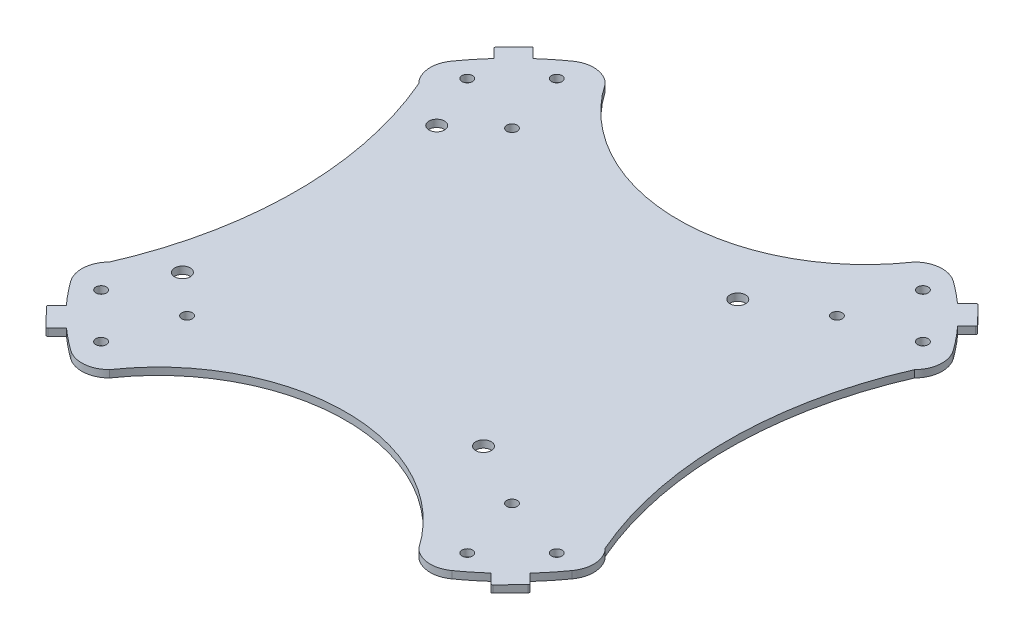
SolidWorks part; units mm, degrees
ref_plane "Front Plane" through (0, 0, 0) normal (0, 0, 1) x (1, 0, 0)
ref_plane "Top Plane" through (0, 0, 0) normal (0, 1, 0) x (1, 0, 0)
ref_plane "Right Plane" through (0, 0, 0) normal (1, 0, 0) x (0, 0, -1)
sketch "Sketch1" plane through (0, 0, 0) normal (0, 1, 0) x (1, 0, 0)
  line L0 (-1000, 0) -> (49000, 0) construction
  line L1 (0, -1000) -> (0, 49000) construction
  line L2 (707.1069, -707.1069) -> (-34648.2322, 34648.2322) construction
  line L3 (-707.1068, -707.1068) -> (34648.2325, 34648.2321) construction
  line L4 (716.0871, -698.1266) -> (0, 17.9605) construction
  line L5 (-698.1265, -716.087) -> (34657.2127, 34639.2518) construction
  line L6 (698.1266, -716.0871) -> (-34657.2125, 34639.2519) construction
  line L7 (-716.087, -698.1265) -> (0, 17.9605) construction
  line L8 (-733.6258, -670.2104) -> (-31.7077, 31.7077) construction
  line L9 (733.9751, -670.5597) -> (22.7274, 40.6879) construction
  line L10 (39.5829, 36.115) -> (36.1358, 39.5583) construction
  line L11 (716.0871, -698.1266) -> (-34639.2519, 34657.2125) construction
  line L12 (35.7817, 39.5534) -> (33.9856, 37.7573) construction
  line L13 (-716.087, -698.1265) -> (34639.2522, 34657.2124) construction
  line L14 (39.5739, 35.7609) -> (37.7573, 33.9856) construction
  line L15 (39.5382, -36.1548) -> (36.0819, -39.6111) construction
  line L16 (39.5078, -35.8322) -> (37.7118, -34.0362) construction
  line L17 (-35.9968, -39.6764) -> (-39.3444, -36.2512) construction
  line L18 (-37.6038, -34.1555) -> (-39.3423, -35.894) construction
  line L19 (35.7129, -39.6171) -> (33.9376, -37.8006) construction
  line L20 (-35.6141, -39.7036) -> (-33.8181, -37.9075) construction
  line L21 (-39.7221, 35.8999) -> (-36.251, 39.2922) construction
  line L22 (-34.2033, 37.5603) -> (-35.8918, 39.2881) construction
  line L24 (-37.9528, 33.7672) -> (-39.7242, 35.5386) construction
  line L25 (-44.6575, -41.2092) -> (-46.396, -42.9477)
  line L26 (-43.0506, -46.7302) -> (-46.3981, -43.3049)
  line L27 (-42.6678, -46.7573) -> (-40.8718, -44.9612)
  line L28 (42.6678, -46.7573) -> (40.8718, -44.9612)
  line L29 (43.0506, -46.7302) -> (46.3981, -43.3049)
  line L30 (-39.4203, -35.9308) -> (-37.6038, -34.1555) [skipped]
  line L31 (-39.7488, 35.5633) -> (-37.9528, 33.7672) [skipped]
  line L32 (-35.9786, 39.3768) -> (-34.2033, 37.5603) [skipped]
  line L33 (44.6575, -41.2092) -> (46.396, -42.9477)
  line L35 (-44.6575, 41.2092) -> (-46.396, 42.9477)
  line L36 (-43.0506, 46.7302) -> (-46.3981, 43.3049)
  line L37 (-42.6678, 46.7573) -> (-40.8718, 44.9612)
  line L38 (44.6575, 41.2092) -> (46.396, 42.9477)
  line L39 (43.0506, 46.7302) -> (46.3981, 43.3049)
  line L40 (42.6678, 46.7573) -> (40.8718, 44.9612)
  arc A0 (-29.6486, 41.2505) -> (-34.2033, 37.5603) centre (0, 0) ccw construction
  arc A1 (-22.7274, 40.6879) -> (-29.6486, 41.2505) centre (-26.519, 36.8963) ccw construction
  arc A2 (-40.6879, 22.7274) -> (-41.2505, 29.6486) centre (-36.8963, 26.519) cw construction
  arc A3 (22.7274, 40.6879) -> (29.6486, 41.2505) centre (26.519, 36.8963) cw construction
  arc A4 (40.6879, 22.7274) -> (41.2505, 29.6486) centre (36.8963, 26.519) ccw construction
  arc A5 (40.6879, -22.7274) -> (41.2505, -29.6486) centre (36.8963, -26.519) cw construction
  arc A6 (22.7274, -40.6879) -> (29.6486, -41.2505) centre (26.519, -36.8963) ccw construction
  arc A7 (-22.7274, -40.6879) -> (-29.6486, -41.2505) centre (-26.519, -36.8963) cw construction
  arc A8 (-40.6879, -22.7274) -> (-41.2505, -29.6486) centre (-36.8963, -26.519) ccw construction
  arc A9 (-22.7274, 40.6879) -> (22.7274, 40.6879) centre (0, 66.2866) ccw construction
  arc A10 (40.6879, 22.7274) -> (40.6879, -22.7274) centre (66.2866, 0) ccw construction
  arc A11 (22.7274, -40.6879) -> (-22.7274, -40.6879) centre (0, -66.2866) ccw construction
  arc A12 (-40.6879, -22.7274) -> (-40.6879, 22.7274) centre (-66.2866, 0) ccw construction
  arc A13 (-29.6486, 41.2505) -> (-34.2033, 37.5603) centre (0, 0) ccw construction
  arc A14 (41.2505, 29.6486) -> (37.7573, 33.9856) centre (0, 0) ccw construction
  arc A15 (41.2505, 29.6486) -> (37.7573, 33.9856) centre (0, 0) ccw construction
  arc A16 (29.6486, -41.2505) -> (33.9376, -37.8006) centre (0, 0) ccw construction
  arc A17 (29.6486, -41.2505) -> (33.9376, -37.8006) centre (0, 0) ccw construction
  arc A18 (-41.2505, -29.6486) -> (-37.6038, -34.1555) centre (0, 0) ccw construction
  arc A19 (-41.2505, -29.6486) -> (-37.6038, -34.1555) centre (0, 0) ccw construction
  arc A20 (33.9856, 37.7573) -> (29.6486, 41.2505) centre (0, 0) ccw construction
  arc A21 (33.9856, 37.7573) -> (29.6486, 41.2505) centre (0, 0) ccw construction
  arc A22 (37.7118, -34.0362) -> (41.2505, -29.6486) centre (0, 0) ccw construction
  arc A23 (37.7118, -34.0362) -> (41.2505, -29.6486) centre (0, 0) ccw construction
  arc A24 (-33.8181, -37.9075) -> (-29.6486, -41.2505) centre (0, 0) ccw construction
  arc A25 (-33.8181, -37.9075) -> (-29.6486, -41.2505) centre (0, 0) ccw construction
  arc A26 (-37.9528, 33.7672) -> (-41.2505, 29.6486) centre (0, 0) ccw construction
  arc A27 (-37.9528, 33.7672) -> (-41.2505, 29.6486) centre (0, 0) ccw construction
  arc A28 (-35.6141, -39.7036) -> (-35.9968, -39.6764) centre (-35.7937, -39.5239) cw construction
  arc A29 (-39.3423, -35.894) -> (-39.3444, -36.2512) centre (-39.1627, -36.0736) ccw construction
  arc A30 (35.7129, -39.6171) -> (36.0819, -39.6111) centre (35.8945, -39.4396) ccw construction
  arc A31 (39.5078, -35.8322) -> (39.5382, -36.1548) centre (39.3282, -36.0118) cw construction
  arc A32 (39.5739, 35.7609) -> (39.5829, 36.115) centre (39.3964, 35.9426) ccw construction
  arc A33 (36.1358, 39.5583) -> (35.7817, 39.5534) centre (35.9613, 39.3738) ccw construction
  arc A34 (-39.7221, 35.8999) -> (-39.7242, 35.5386) centre (-39.5446, 35.7182) ccw construction
  arc A35 (-36.251, 39.2922) -> (-35.8918, 39.2881) centre (-36.0735, 39.1105) cw construction
  circle A36 centre (-28.2202, 36.8412) radius 1.016 construction
  circle A37 centre (-36.8412, 28.2202) radius 1.016 construction
  circle A38 centre (-24.2455, 24.2455) radius 1.016 construction
  circle A39 centre (28.2202, 36.8412) radius 1.016 construction
  circle A40 centre (36.8412, 28.2202) radius 1.016 construction
  circle A41 centre (24.2455, 24.2455) radius 1.016 construction
  circle A42 centre (36.8412, -28.2202) radius 1.016 construction
  circle A43 centre (28.2202, -36.8412) radius 1.016 construction
  circle A44 centre (24.2455, -24.2455) radius 1.016 construction
  circle A45 centre (-28.2202, -36.8412) radius 1.016 construction
  circle A46 centre (-36.8412, -28.2202) radius 1.016 construction
  circle A47 centre (-24.2455, -24.2455) radius 1.016 construction
  circle A48 centre (0, 0) radius 6.1441 construction
  arc A49 (-47.7417, -29.7811) -> (-48.3042, -36.7023) centre (-43.9501, -33.5727) ccw
  arc A50 (-48.3042, -36.7023) -> (-44.6575, -41.2092) centre (-7.0537, -7.0537) ccw
  arc A51 (-42.6678, -46.7573) -> (-43.0506, -46.7302) centre (-42.8474, -46.5777) cw
  arc A52 (-46.396, -42.9477) -> (-46.3981, -43.3049) centre (-46.2164, -43.1273) ccw
  arc A53 (-29.7811, -47.7417) -> (-36.7023, -48.3042) centre (-33.5727, -43.9501) cw
  arc A54 (-40.8718, -44.9612) -> (-36.7023, -48.3042) centre (-7.0537, -7.0537) ccw
  circle A55 centre (-35.2739, -43.8949) radius 1.016
  arc A56 (-40.8718, -44.9612) -> (-36.7023, -48.3042) centre (-7.0537, -7.0537) ccw construction
  circle A57 centre (-43.8949, -35.2739) radius 1.016
  circle A58 centre (-31.2992, -31.2992) radius 1.016
  arc A59 (42.6678, -46.7573) -> (43.0506, -46.7302) centre (42.8474, -46.5777) ccw
  arc A60 (46.396, -42.9477) -> (46.3981, -43.3049) centre (46.2164, -43.1273) cw
  circle A61 centre (43.8949, -35.2739) radius 1.016
  arc A62 (48.3042, -36.7023) -> (44.6575, -41.2092) centre (7.0537, -7.0537) cw
  arc A63 (47.7417, -29.7811) -> (48.3042, -36.7023) centre (43.9501, -33.5727) cw
  arc A64 (29.7811, -47.7417) -> (36.7023, -48.3042) centre (33.5727, -43.9501) ccw
  arc A65 (40.8718, -44.9612) -> (36.7023, -48.3042) centre (7.0537, -7.0537) cw
  circle A66 centre (35.2739, -43.8949) radius 1.016
  circle A67 centre (31.2992, -31.2992) radius 1.016
  arc A68 (-46.396, 42.9477) -> (-46.3981, 43.3049) centre (-46.2164, 43.1273) cw
  arc A69 (-42.6678, 46.7573) -> (-43.0506, 46.7302) centre (-42.8474, 46.5777) ccw
  arc A70 (-40.8718, 44.9612) -> (-36.7023, 48.3042) centre (-7.0537, 7.0537) cw
  arc A71 (-48.3042, 36.7023) -> (-44.6575, 41.2092) centre (-7.0537, 7.0537) cw
  arc A72 (-47.7417, 29.7811) -> (-48.3042, 36.7023) centre (-43.9501, 33.5727) cw
  arc A73 (-29.7811, 47.7417) -> (-36.7023, 48.3042) centre (-33.5727, 43.9501) ccw
  circle A74 centre (-35.2739, 43.8949) radius 1.016
  circle A75 centre (-31.2992, 31.2992) radius 1.016
  circle A76 centre (-43.8949, 35.2739) radius 1.016
  arc A77 (48.3042, 36.7023) -> (44.6575, 41.2092) centre (7.0537, 7.0537) ccw
  arc A78 (47.7417, 29.7811) -> (48.3042, 36.7023) centre (43.9501, 33.5727) ccw
  arc A79 (46.396, 42.9477) -> (46.3981, 43.3049) centre (46.2164, 43.1273) ccw
  arc A80 (42.6678, 46.7573) -> (43.0506, 46.7302) centre (42.8474, 46.5777) cw
  arc A81 (40.8718, 44.9612) -> (36.7023, 48.3042) centre (7.0537, 7.0537) ccw
  arc A82 (29.7811, 47.7417) -> (36.7023, 48.3042) centre (33.5727, 43.9501) cw
  circle A83 centre (43.8949, 35.2739) radius 1.016
  circle A84 centre (35.2739, 43.8949) radius 1.016
  circle A85 centre (31.2992, 31.2992) radius 1.016
  arc A86 (-29.7811, -47.7417) -> (29.7811, -47.7417) centre (0, -68.1673) cw
  arc A87 (29.7811, 47.7417) -> (-29.7811, 47.7417) centre (0, 68.1673) cw
  arc A88 (47.7417, 29.7811) -> (47.7417, -29.7811) centre (116.5754, 0) ccw
  arc A89 (-47.7417, 29.7811) -> (-47.7417, -29.7811) centre (-116.5754, 0) cw
  circle A90 centre (-39, 24.5) radius 1.5
  circle A91 centre (19, 24.5) radius 1.5
  circle A92 centre (19.003, -24.4994) radius 1.5
  circle A93 centre (-39, -24.5) radius 1.5
  point P46 (0, 0)
  point P60 (0, 0)
  point P75 (-0.048, -0.2069)
  point P83 (41.6473, 37.8756)
  point P86 (37.8756, 41.6473)
  point P94 (-39, 24.5)
  point P120 (0, 0)
  point P208 (-39, -24.5)
  point P210 (19, 24.5)
  point P212 (19.003, -24.4994)
  dimension "D1" = 12.7
  dimension "D3" = 4
  dimension "D4" = 4
  dimension "D7" = 0.254
  dimension "D8" = 50.8
  dimension "D10" = 0.254
  dimension "D9" = 0.254
  dimension "D13" = 13.208
  dimension "D15" = 2
  dimension "D16" = 75
  dimension "D17" = 3
  dimension "D5" = 2.667
  dimension "D11" = 12.192
  dimension "D12" = 7.366
  dimension "D2" = 12.7
  dimension "D6" = 4
  dimension "D14" = 4
extrude "Boss-Extrude1" add sketch "Sketch1" along normal blind 1.397
